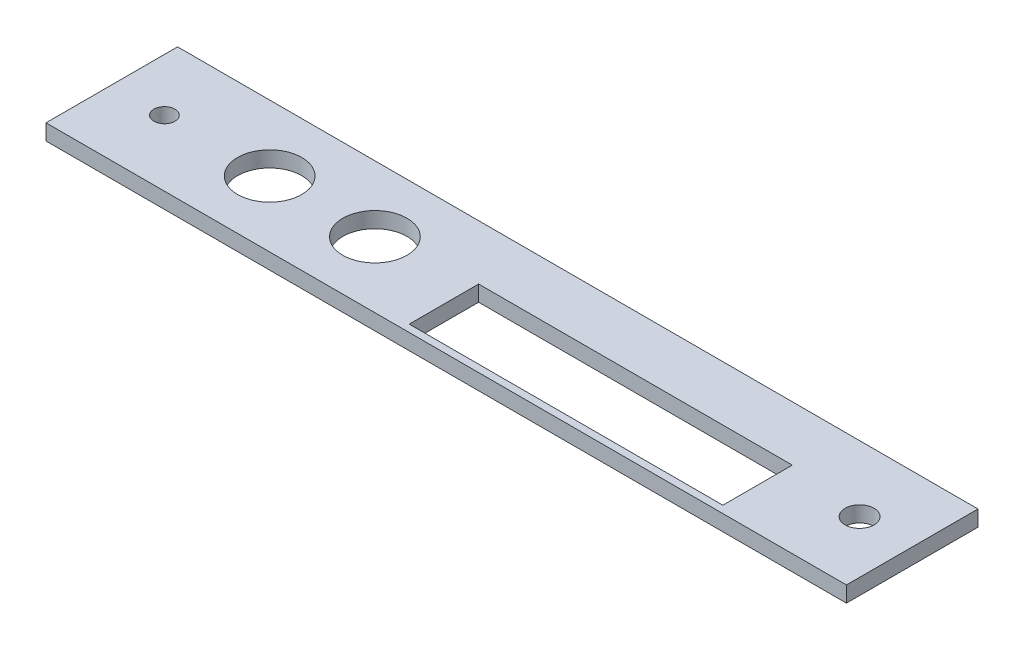
SolidWorks part; units mm, degrees
material "Custom Plastic"
ref_plane "Plan de face" through (0, 0, 0) normal (0, 0, 1) x (1, 0, 0)
ref_plane "Plan de dessus" through (0, 0, 0) normal (0, 1, 0) x (1, 0, 0)
ref_plane "Plan de droite" through (0, 0, 0) normal (1, 0, 0) x (0, 0, -1)
sketch "Esquisse1" plane through (0, 0, 0) normal (0, 1, 0) x (1, 0, 0)
  line L3 (-76.5453, -14.573) -> (75.5547, -14.573) construction
  line L5 (-76.7453, 10.427) -> (-76.7453, -14.573) construction
  line L6 (-86.2453, 10.427) -> (78.7547, 10.427) construction
  line L10 (75.7547, -14.573) -> (75.7547, 10.427) construction
  line L12 (-76.5453, -14.573) -> (75.5547, -14.573)
  line L13 (65.5547, -2.073) -> (75.5547, -2.073) construction
  line L15 (-86.2453, -14.573) -> (78.7547, -14.573) construction
  line L20 (-66.5453, -2.073) -> (-76.5453, -2.073) construction
  line L26 (65.5547, -45.0903) -> (65.5547, -50045.0903) construction
  line L28 (-66.5453, 45.927) -> (-66.5453, 0.927) construction
  line L36 (-76.5453, 10.427) -> (75.5547, 10.427)
  line L37 (75.5547, 10.427) -> (75.5547, -14.573)
  line L44 (-76.5453, 10.427) -> (-76.5453, -14.573)
  circle A12 centre (65.5547, -2.073) radius 2.75
  circle A15 centre (-66.5453, -2.073) radius 2
  dimension "D3" = 4
  dimension "D4" = 0.2
  dimension "D5" = 5.5
  dimension "D1" = 10
  dimension "D2" = 0.2
extrude "Boss.-Extru.1" add sketch "Esquisse1" along normal blind 3
sketch "Esquisse3" plane through (0, 0, 0) normal (0, 1, 0) x (1, 0, 0)
  line L40 (-76.5453, -2.073) -> (-26.5453, -2.073) construction
  line L41 (-76.5453, 10.427) -> (-76.5453, -14.573) construction
  line L43 (-8.9081, 0) -> (50.6905, 0)
  line L44 (-8.9081, 0) -> (-8.9081, -13.19)
  line L45 (-8.9081, -13.19) -> (50.6905, -13.19)
  line L46 (50.6905, 0) -> (50.6905, -13.19)
  circle A5 centre (-46.5453, -2.073) radius 6.1
  circle A6 centre (-26.5453, -2.073) radius 6.1
  dimension "D13" = 12.2
  dimension "D14" = 20
  dimension "D15" = 30
extrude "Enlèv. mat.-Extru.2" cut sketch "Esquisse3" along normal through all
